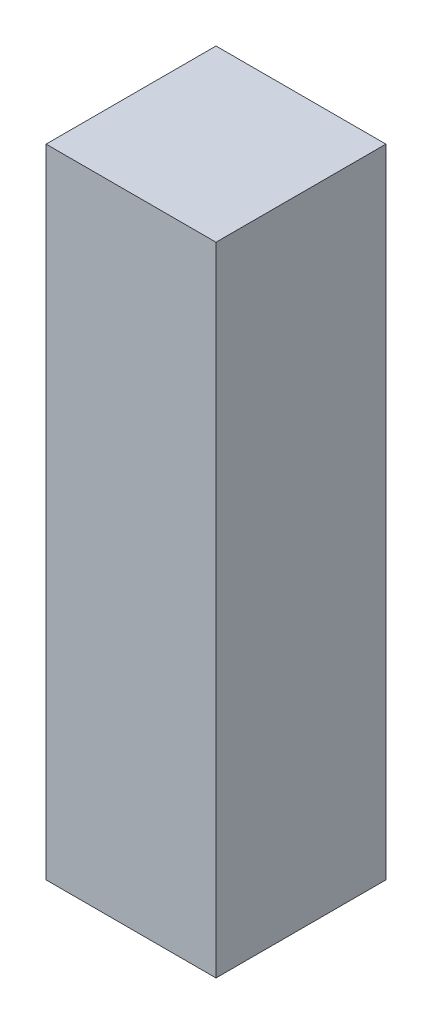
SolidWorks part; units mm, degrees
material "Titanium"
ref_plane "Front Plane" through (0, 0, 0) normal (0, 0, 1) x (1, 0, 0)
ref_plane "Top Plane" through (0, 0, 0) normal (0, 1, 0) x (1, 0, 0)
ref_plane "Right Plane" through (0, 0, 0) normal (1, 0, 0) x (0, 0, -1)
sketch "Sketch2" plane through (0, 0, 0) normal (0, 1, 0) x (1, 0, 0)
  line L1 (-4, -4) -> (4, -4)
  line L2 (-4, -4) -> (-4, 4)
  line L3 (-4, 4) -> (4, 4)
  line L4 (4, -4) -> (4, 4)
  line L5 (-4, -4) -> (4, 4) construction
  line L6 (-4, 4) -> (4, -4) construction
  point P0 (0, 0)
  dimension "D1" = 8
  dimension "D2" = 8
extrude "Boss-Extrude1" add sketch "Sketch2" along normal blind 30
